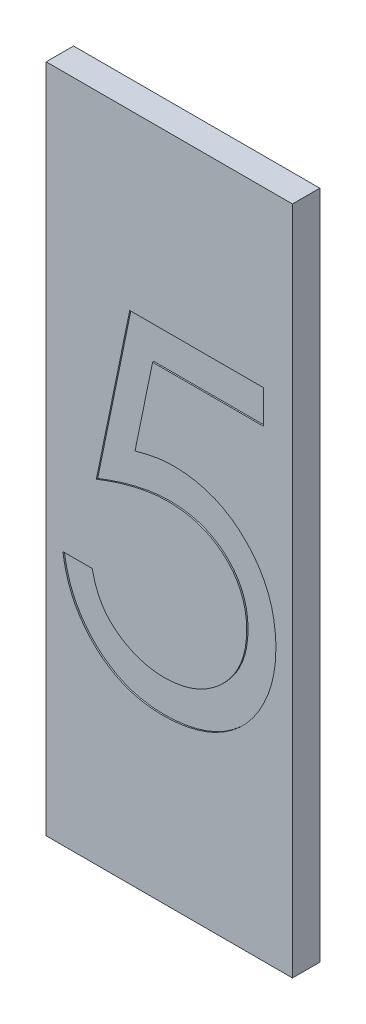
SolidWorks part; units mm, degrees
ref_plane "正面" through (0, 0, 0) normal (0, 0, 1) x (1, 0, 0)
ref_plane "平面" through (0, 0, 0) normal (0, 1, 0) x (1, 0, 0)
ref_plane "右側面" through (0, 0, 0) normal (1, 0, 0) x (0, 0, -1)
sketch "ｽｹｯﾁ1" plane through (0, 0, 0) normal (0, 0, 1) x (1, 0, 0)
  line L0 (18, 0) -> (0, 0)
  line L1 (18, 49) -> (0, 49)
  line L2 (0, 0) -> (0, 49)
  line L4 (18, 0) -> (18, 49)
extrude "ﾎﾞｽ - 押し出し1" add sketch "ｽｹｯﾁ1" along normal blind 2
sketch "ｽｹｯﾁ2" plane through (0, 0, 2) normal (0, 0, 1) x (1, 0, 0)
  text T0 "5" font "Century Gothic" height in points 90
extrude "ｶｯﾄ - 押し出し1" cut sketch "ｽｹｯﾁ2" against normal blind 0.1
